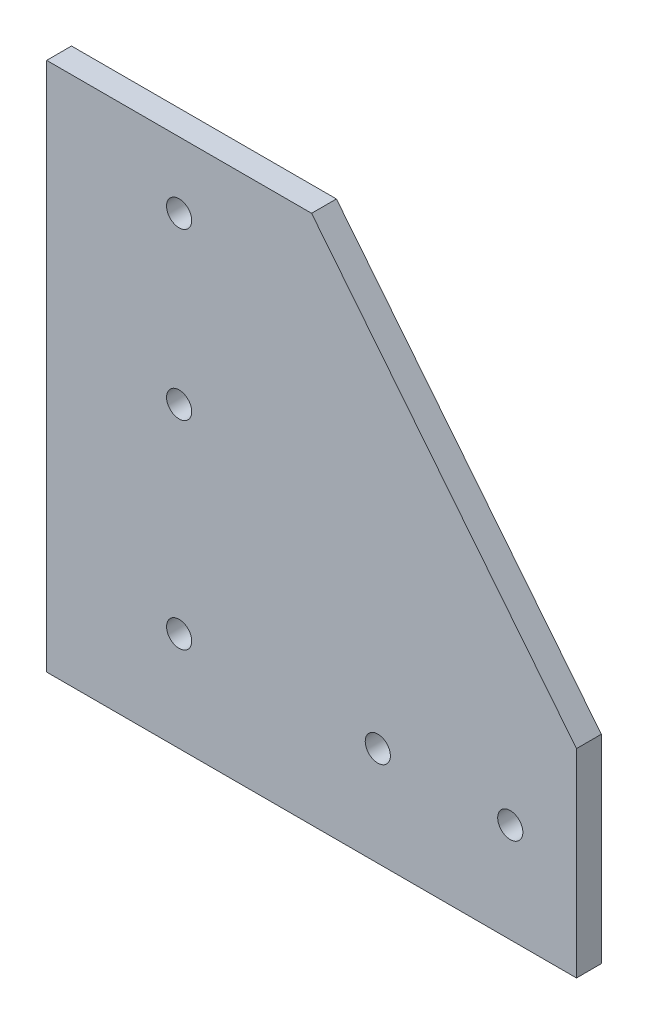
SolidWorks part; units mm, degrees
ref_plane "Front Plane" through (0, 0, 0) normal (0, 0, 1) x (1, 0, 0)
ref_plane "Top Plane" through (0, 0, 0) normal (0, 1, 0) x (1, 0, 0)
ref_plane "Right Plane" through (0, 0, 0) normal (1, 0, 0) x (0, 0, -1)
sketch "Sketch1" plane through (0, 0, 0) normal (0, 0, 1) x (1, 0, 0)
  line L0 (50.8, 101.6) -> (101.6, 38.1)
  line L1 (0, 0) -> (101.6, 0)
  line L2 (0, 0) -> (0, 101.6)
  line L3 (0, 101.6) -> (101.6, 101.6)
  line L4 (101.6, 0) -> (101.6, 101.6)
  circle A0 centre (25.4, 19.05) radius 2.413
  circle A1 centre (25.4, 57.15) radius 2.413
  circle A2 centre (25.4, 88.9) radius 2.413
  circle A3 centre (88.9, 19.05) radius 2.413
  circle A4 centre (63.5, 19.05) radius 2.413
  point P17 (0, 0)
  dimension "D6" = 4.826
  dimension "D12" = 4.826
  dimension "D13" = 4.826
  dimension "D14" = 4.826
  dimension "D15" = 4.826
  dimension "D1" = 101.6
  dimension "D2" = 101.6
  dimension "D3" = 50.8
  dimension "D4" = 38.1
  dimension "D5" = 12.7
  dimension "D7" = 19.05
  dimension "D8" = 38.1
  dimension "D9" = 25.4
  dimension "D10" = 25.4
  dimension "D11" = 25.4
  dimension "D16" = 12.7
  dimension "D17" = 25.4
  dimension "D18" = 19.05
  dimension "D19" = 19.05
extrude "Boss-Extrude1" add sketch "Sketch1" along normal blind 4.7625 contours L1 L4 L0 L3 L2 A4 A3 A2 A1 A0
